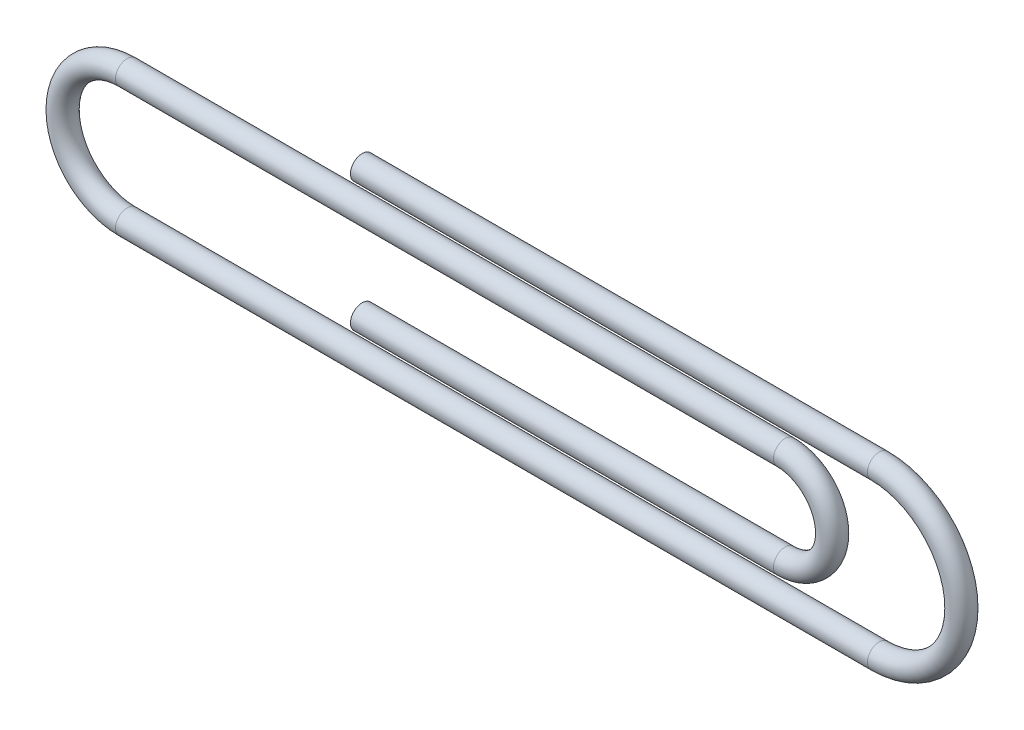
SolidWorks part; units mm, degrees
ref_plane "Front Plane" through (0, 0, 0) normal (0, 0, 1) x (1, 0, 0)
ref_plane "Top Plane" through (0, 0, 0) normal (0, 1, 0) x (1, 0, 0)
ref_plane "Right Plane" through (0, 0, 0) normal (1, 0, 0) x (0, 0, -1)
sketch "Sketch1" plane through (0, 0, 0) normal (0, 0, 1) x (1, 0, 0)
  line L0 (-7.0246, 0) -> (14.9754, 0)
  line L2 (14.9754, -7) -> (-17.0246, -7)
  line L4 (-17.0246, -1.5) -> (10.9754, -1.5)
  line L6 (10.9754, -5.5) -> (-7.0246, -5.5)
  arc A0 (14.9754, 0) -> (14.9754, -7) centre (14.9754, -3.5) cw
  arc A1 (-17.0246, -1.5) -> (-17.0246, -7) centre (-17.0246, -4.25) ccw
  arc A2 (10.9754, -1.5) -> (10.9754, -5.5) centre (10.9754, -3.5) cw
  point P12 (0, 0)
  point P13 (0, 0)
  point P14 (-11.1667, -5.5)
  point P15 (0, 0)
  point P16 (0, 0)
  dimension "D1" = 3.5
  dimension "D2" = 4
  dimension "D3" = 32
  dimension "D4" = 22
  dimension "D5" = 4
  dimension "D6" = 1.5
  dimension "D7" = 1.5
  dimension "D8" = 10
sweep "Sweep1" add path "Sketch1" circular profile diameter 1 parameters "D3"=1
